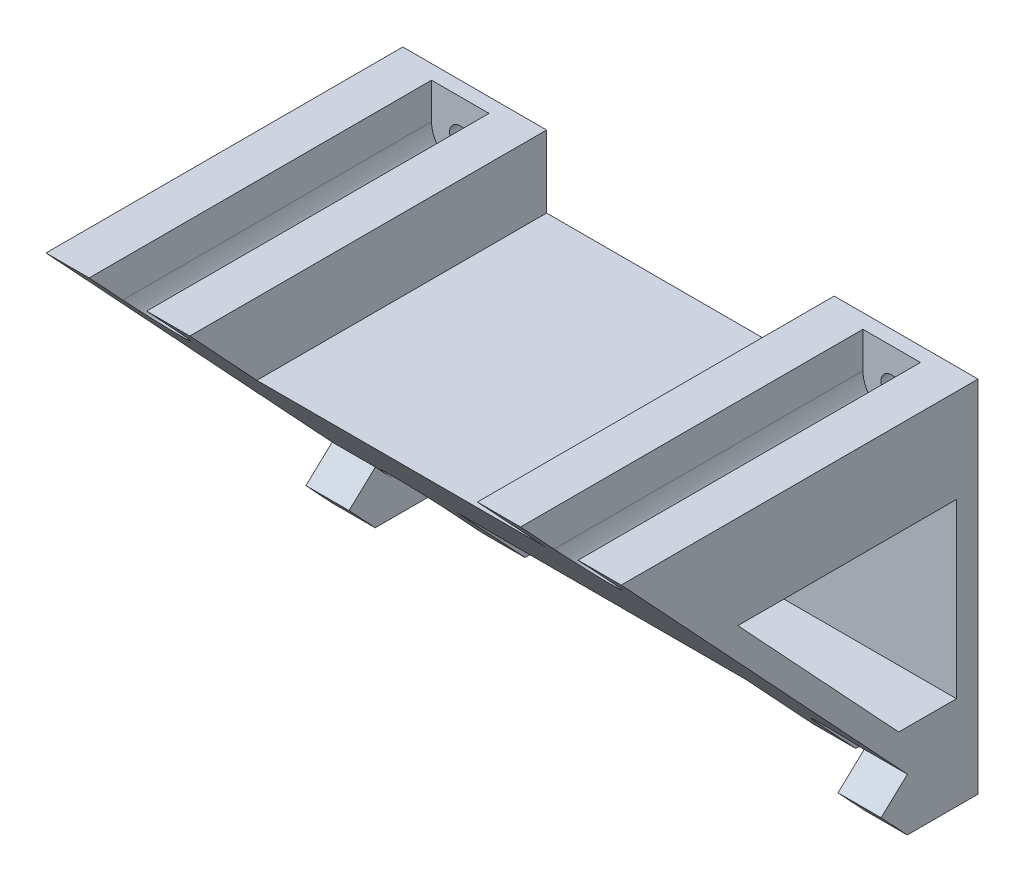
SolidWorks part; units mm, degrees
ref_plane "前视基准面" through (0, 0, 0) normal (0, 0, 1) x (1, 0, 0)
ref_plane "上视基准面" through (0, 0, 0) normal (0, 1, 0) x (1, 0, 0)
ref_plane "右视基准面" through (0, 0, 0) normal (1, 0, 0) x (0, 0, -1)
sketch "草图1" plane through (0, 0, 0) normal (0, 0, 1) x (1, 0, 0)
  line L0 (0, 0) -> (0, 50)
  line L1 (20, 50) -> (20, 40)
  line L2 (60, 40) -> (20, 40)
  line L3 (60, 50) -> (60, 40)
  line L4 (20, 50) -> (0, 50)
  line L5 (60, 50) -> (80, 50)
  line L6 (80, 50) -> (80, 0)
  line L7 (80, 0) -> (60, 0)
  line L8 (60, 0) -> (60, 10)
  line L9 (60, 10) -> (20, 10)
  line L10 (20, 10) -> (20, 0)
  line L11 (20, 0) -> (0, 0)
  point P13 (0, 0)
  point P14 (0, 0)
  dimension "D1" = 50
  dimension "D2" = 20
  dimension "D3" = 40
  dimension "D4" = 20
  dimension "D5" = 20
  dimension "D6" = 40
  dimension "D7" = 20
  dimension "D8" = 10
  dimension "D10" = 10
extrude "凸台-拉伸2" add sketch "草图1" along normal blind 2
sketch "草图3" plane through (0, 0, 2) normal (0, 0, 1) x (1, 0, 0)
  line L0 (10, 5) -> (10, 0) construction
  line L2 (20, 0) -> (0, 0) construction
  line L3 (10, 50) -> (10, 45) construction
  line L4 (20, 50) -> (0, 50) construction
  line L5 (70, 50) -> (70, 45) construction
  line L6 (60, 50) -> (80, 50) construction
  line L7 (70, 0) -> (70, 5) construction
  line L8 (80, 0) -> (60, 0) construction
  circle A1 centre (10, 45) radius 1.5
  circle A2 centre (10, 5) radius 1.5
  circle A3 centre (70, 45) radius 1.5
  circle A4 centre (70, 5) radius 1.5
  point P20 (0, 0)
  dimension "D1" = 3
  dimension "D4" = 3
  dimension "D5" = 3
  dimension "D6" = 3
  dimension "D2" = 40
  dimension "D3" = 40
  dimension "D7" = 60
  dimension "D8" = 60
  dimension "D9" = 10
  dimension "D10" = 10
  dimension "D11" = 10
  dimension "D12" = 10
extrude "切除-拉伸1" cut sketch "草图3" against normal through all
sketch "草图5" plane through (0, 0, 2) normal (0, 0, 1) x (1, 0, 0)
  line L0 (0, 50) -> (6, 50)
  line L1 (20, 50) -> (0, 50) construction
  line L2 (6, 50) -> (6, 45)
  line L3 (14, 45) -> (14, 50)
  line L4 (14, 50) -> (20, 50)
  line L5 (20, 50) -> (20, 40)
  line L6 (20, 40) -> (60, 40)
  line L7 (60, 40) -> (60, 50)
  line L8 (60, 50) -> (66, 50)
  line L9 (60, 50) -> (80, 50) construction
  line L10 (66, 50) -> (66, 45)
  line L11 (74, 45) -> (74, 50)
  line L12 (74, 50) -> (80, 50)
  line L13 (80, 50) -> (80, 0)
  line L14 (80, 0) -> (74, 0)
  line L15 (80, 0) -> (60, 0) construction
  line L16 (74, 0) -> (74, 5)
  line L17 (66, 5) -> (66, 0)
  line L18 (66, 0) -> (60, 0)
  line L19 (60, 0) -> (60, 10)
  line L20 (60, 10) -> (20, 10)
  line L21 (20, 10) -> (20, 0)
  line L22 (20, 0) -> (14, 0)
  line L23 (20, 0) -> (0, 0) construction
  line L24 (14, 0) -> (14, 5)
  line L25 (6, 5) -> (6, 0)
  line L26 (6, 0) -> (0, 0)
  line L27 (0, 0) -> (0, 50)
  arc A0 (6, 45) -> (14, 45) centre (10, 45) ccw
  arc A1 (66, 45) -> (74, 45) centre (70, 45) ccw
  arc A2 (74, 5) -> (66, 5) centre (70, 5) ccw
  arc A3 (14, 5) -> (6, 5) centre (10, 5) ccw
  dimension "D5" = 4
  dimension "D6" = 4
  dimension "D7" = 4
  dimension "D8" = 4
  dimension "D1" = 5
  dimension "D2" = 5
  dimension "D3" = 5
  dimension "D4" = 5
  dimension "D9" = 10
  dimension "D10" = 10
  dimension "D11" = 10
  dimension "D12" = 10
extrude "凸台-拉伸3" add sketch "草图5" along normal blind 1
draft "拔模4" type of draft neutral plane draft angle 43 faces to draft 1 face at (40, 25, 3) neutral plane through (20, 0, 2) neutral plane normal (0, -1, 0) parameters "D1"=43
sketch "草图6" plane through (0, -1.4963, 1.6046) normal (0, -0.682, 0.7314) x (1, 0, 0)
  line L0 (6, 2.046) -> (6, 12.046)
  line L1 (6, 2.046) -> (6, 8.8826) construction
  line L2 (6, 12.046) -> (0, 12.046)
  line L3 (0, 70.4124) -> (0, 2.046) construction
  line L4 (0, 12.046) -> (0, 2.046)
  line L5 (0, 2.046) -> (6, 2.046)
  dimension "D1" = 10
  dimension "D2" = 6
extrude "凸台-拉伸4" add sketch "草图6" along normal blind 5
sketch "草图7" plane through (0, -1.4963, 1.6046) normal (0, -0.682, 0.7314) x (1, 0, 0)
  line L0 (74, 2.046) -> (80, 2.046)
  line L1 (80, 2.046) -> (80, 12.046)
  line L2 (80, 2.046) -> (80, 70.4124) construction
  line L3 (80, 12.046) -> (74, 12.046)
  line L4 (74, 12.046) -> (74, 2.046)
  dimension "D1" = 10
  dimension "D2" = 6
extrude "凸台-拉伸5" add sketch "草图7" along normal blind 5 contours L4 L0 L1 L3
sketch "草图8" plane through (80, 0, 0) normal (1, 0, 0) x (0, 0, -1)
  line L0 (-3, 0) -> (-9.8366, 0)
  line L1 (-6.6568, -3.41) -> (-13.4768, 3.9035) construction
  line L2 (-9.8366, 0) -> (-6.6568, -3.41)
  line L3 (-6.6568, -3.41) -> (-3, 0)
extrude "切除-拉伸2" cut sketch "草图8" against normal through all
sketch "草图11" plane through (80, 0, 0) normal (1, 0, 0) x (0, 0, -1)
  line L0 (-3, 37) -> (-3, 13)
  line L1 (-3, 13) -> (-11.0207, 13)
  line L2 (-11.0207, 13) -> (-33.4011, 37)
  line L3 (-33.4011, 37) -> (-3, 37)
  line L4 (0, 50) -> (0, 0) construction
  line L6 (-49.6258, 50) -> (0, 50) construction
  line L7 (-9.8366, 0) -> (0, 0) construction
  line L9 (-9.82, 7.3135) -> (-49.6258, 50) construction
  dimension "D1" = 3
  dimension "D2" = 13
  dimension "D3" = 13
  dimension "D4" = 3
  dimension "D5" = 3
extrude "切除-拉伸4" cut sketch "草图11" against normal through all contours L3 L0 L1 L2
